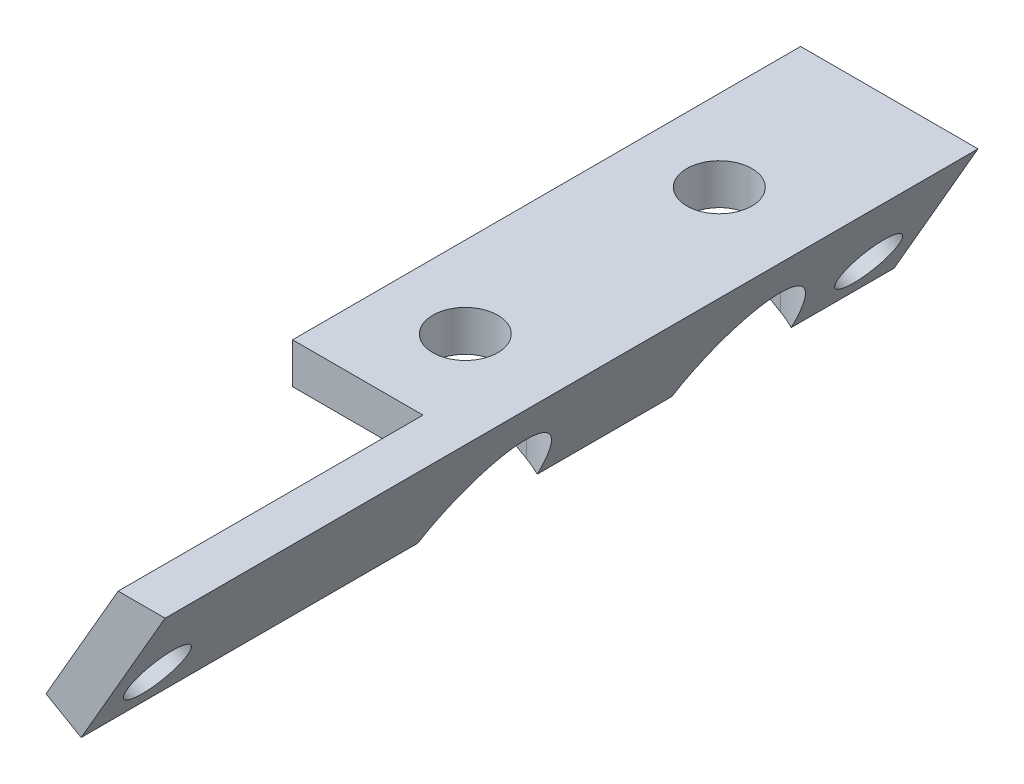
SolidWorks part; units mm, degrees
material "PET"
ref_plane "Front Plane" through (0, 0, 0) normal (0, 0, 1) x (1, 0, 0)
ref_plane "Top Plane" through (0, 0, 0) normal (0, 1, 0) x (1, 0, 0)
ref_plane "Right Plane" through (0, 0, 0) normal (1, 0, 0) x (0, 0, -1)
sketch "Sketch1" plane through (0, 0, 0) normal (0, 0, 1) x (1, 0, 0)
  line L0 (0, 0) -> (4.1281, 7.15)
  line L1 (4.1281, 7.15) -> (-4.6, 7.15)
  line L2 (0, 0) -> (-1.7321, 1)
  line L3 (-1.7321, 1) -> (0.664, 5.15)
  line L4 (0.664, 5.15) -> (-4.6, 5.15)
  line L5 (-4.6, 5.15) -> (-4.6, 7.15)
  dimension "D1" = 2
  dimension "D2" = 60
  dimension "D3" = 7.15
  dimension "D4" = 4.6
  dimension "D5" = 2
extrude "Boss-Extrude1" add sketch "Sketch1" along normal blind 25
sketch "Sketch2" plane through (0, 0, 25) normal (0, 0, 1) x (1, 0, 0)
  line L0 (4.1281, 7.15) -> (0, 0)
  line L1 (0, 0) -> (-1.7321, 1)
  line L2 (-1.7321, 1) -> (1.8187, 7.15)
  line L3 (4.1281, 7.15) -> (-4.6, 7.15) construction
  line L4 (1.8187, 7.15) -> (4.1281, 7.15)
extrude "Boss-Extrude2" add sketch "Sketch2" along normal blind 15
sketch "Sketch3" plane through (0, 0, 0) normal (0.866, -0.5, 0) x (0, 0, -1)
  line L0 (-40, 2.5) -> (0, 2.5) construction
  line L1 (-40, 0) -> (-40, 8.2561) construction
  line L2 (0, 0) -> (0, 8.2561) construction
  line L3 (-40, 0) -> (0, 0) construction
  circle A0 centre (-37.5, 2.5) radius 1.5
  circle A1 centre (-2.5, 2.5) radius 1.5
  dimension "D2" = 3
  dimension "D3" = 2.5
  dimension "D4" = 2.5
  dimension "D5" = 3
  dimension "D1" = 2.5
extrude "Cut-Extrude1" cut sketch "Sketch3" against normal up to next
sketch "Sketch4" plane through (0, 7.15, 0) normal (0, 1, 0) x (1, 0, 0)
  line L0 (1.8187, -25) -> (-4.6, -25) construction
  line L1 (4.1281, 0) -> (-4.6, 0) construction
  line L2 (-0.6, 0) -> (-0.6, -20.5) construction
  line L3 (-4.6, -25) -> (-4.6, 0) construction
  circle A0 centre (-0.6, -8) radius 1.6
  circle A1 centre (-0.6, -20.5) radius 1.6
  dimension "D1" = 3.2
  dimension "D2" = 4.5
  dimension "D3" = 3.2
  dimension "D4" = 8
  dimension "D5" = 4
extrude "Cut-Extrude2" cut sketch "Sketch4" against normal up to next
sketch "Sketch5" plane through (0, 5.15, 0) normal (0, -1, 0) x (1, 0, 0)
  line L0 (-0.6, 23.5) -> (-3.6, 23.5)
  line L1 (-3.6, 23.5) -> (-3.6, 17.5)
  line L2 (-3.6, 17.5) -> (-0.6, 17.5)
  line L3 (-0.6, 11) -> (-3.6, 11)
  line L4 (-3.6, 11) -> (-3.6, 5)
  line L5 (-3.6, 5) -> (-0.6, 5)
  arc A0 (-0.6, 17.5) -> (-0.6, 23.5) centre (-0.6, 20.5) ccw
  arc A1 (-0.6, 5) -> (-0.6, 11) centre (-0.6, 8) ccw
  dimension "D1" = 6
  dimension "D2" = 6
extrude "Cut-Extrude3" cut sketch "Sketch5" along normal through all
